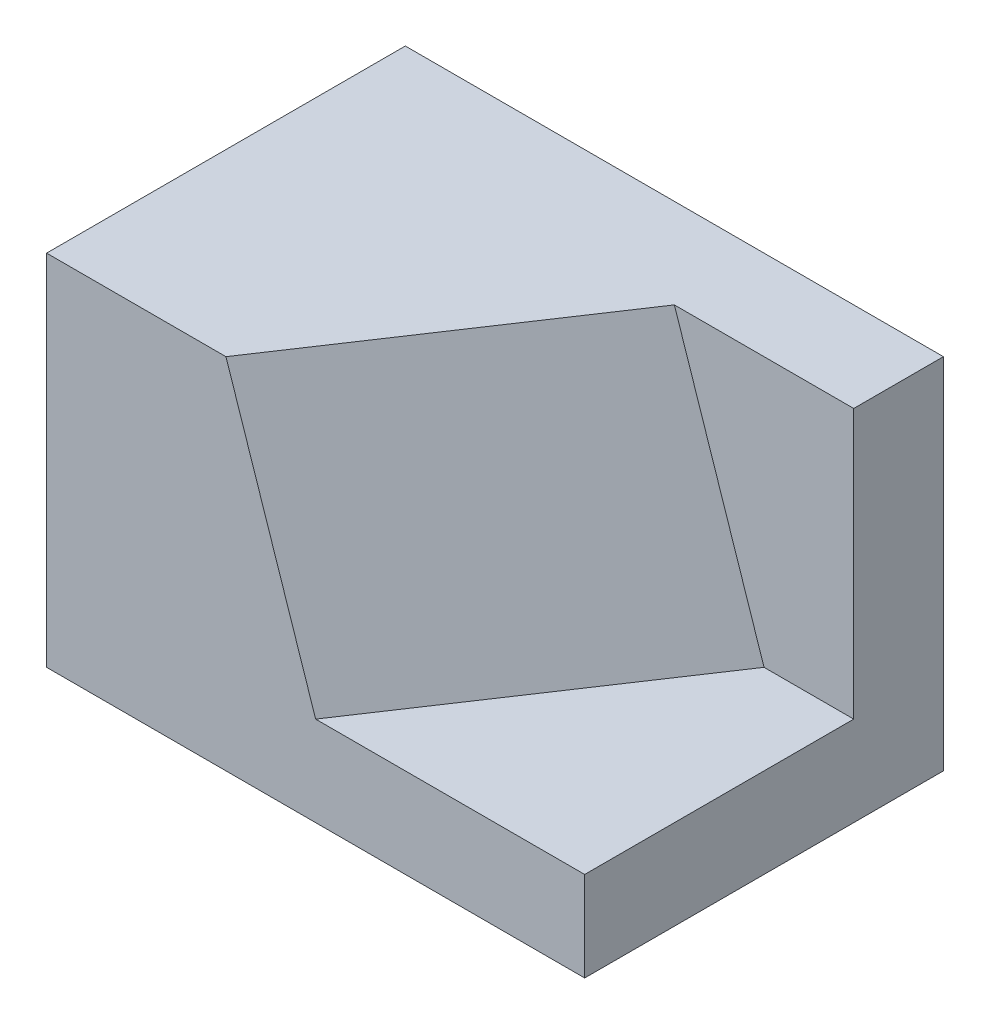
SolidWorks part; units mm, degrees
ref_plane "Front Plane" through (0, 0, 0) normal (0, 0, 1) x (1, 0, 0)
ref_plane "Top Plane" through (0, 0, 0) normal (0, 1, 0) x (1, 0, 0)
ref_plane "Right Plane" through (0, 0, 0) normal (1, 0, 0) x (0, 0, -1)
sketch "Sketch1" plane through (0, 0, 0) normal (0, 0, 1) x (1, 0, 0)
  line L1 (-30, 20) -> (30, 20)
  line L2 (-30, 20) -> (-30, -20)
  line L3 (-30, -20) -> (30, -20)
  line L4 (30, 20) -> (30, -20)
  line L5 (-30, 20) -> (30, -20) construction
  line L6 (-30, -20) -> (30, 20) construction
  point P0 (0, 0)
  dimension "D1" = 40
  dimension "D2" = 60
extrude "Boss-Extrude1" add sketch "Sketch1" along normal blind 10
sketch "Sketch2" plane through (0, 0, 10) normal (0, 0, 1) x (1, 0, 0)
  line L0 (-30, -20) -> (-30, 20)
  line L1 (-30, 20) -> (10, 20)
  line L2 (30, 20) -> (-30, 20) construction
  line L3 (10, 20) -> (20, -10)
  line L4 (20, -10) -> (30, -10)
  line L5 (30, -20) -> (30, 20) construction
  line L6 (30, -10) -> (30, -20)
  line L7 (30, -20) -> (-30, -20)
  dimension "D1" = 10
  dimension "D2" = 10
  dimension "D3" = 40
ref_plane "Plane1" through (0, 0, 40) normal (0, 0, 1) x (1, 0, 0)
sketch "Sketch3" plane through (0, 0, 40) normal (0, 0, 1) x (1, 0, 0)
  line L0 (-10, 20) -> (-30, 20)
  line L1 (-30, 20) -> (10, 20) construction
  line L2 (-30, 20) -> (-30, -20)
  line L3 (-30, -20) -> (30, -20)
  line L4 (30, -20) -> (30, -10)
  line L5 (30, -10) -> (0, -10)
  line L6 (0, -10) -> (-10, 20)
  line L7 (10, 20) -> (20, -10) construction
  dimension "D1" = 30
loft "Loft1" add profiles "Sketch3", "Sketch2"
